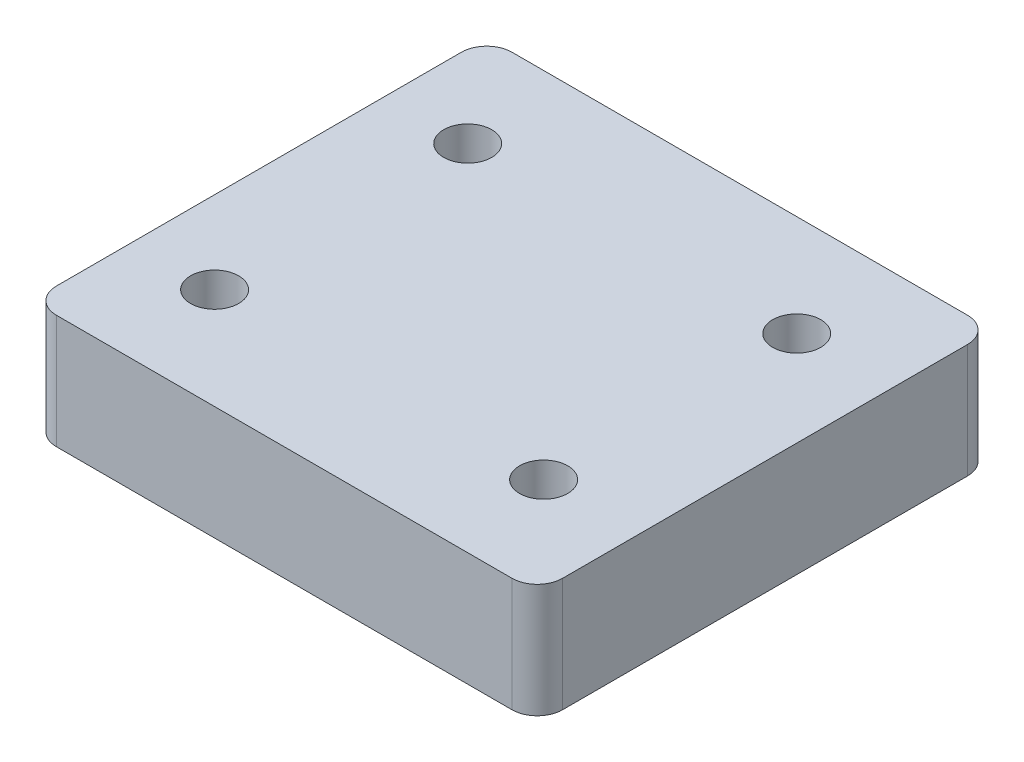
SolidWorks part; units mm, degrees
ref_plane "Front Plane" through (0, 0, 0) normal (0, 0, 1) x (1, 0, 0)
ref_plane "Top Plane" through (0, 0, 0) normal (0, 1, 0) x (1, 0, 0)
ref_plane "Right Plane" through (0, 0, 0) normal (1, 0, 0) x (0, 0, -1)
sketch "Sketch1" plane through (0, 0, 0) normal (0, 1, 0) x (1, 0, 0)
  line L1 (-10.5177, 16.6808) -> (29.4823, 16.6808)
  line L2 (-10.5177, 16.6808) -> (-10.5177, -19.3192)
  line L3 (-10.5177, -19.3192) -> (29.4823, -19.3192)
  line L4 (29.4823, 16.6808) -> (29.4823, -19.3192)
  dimension "D1" = 40
  dimension "D2" = 36
extrude "Boss-Extrude1" add sketch "Sketch1" along normal blind 9
sketch "Sketch2" plane through (0, 9, 0) normal (0, 1, 0) x (1, 0, 0)
  line L1 (-10.5177, -19.3192) -> (29.4823, -19.3192) construction
  line L2 (29.4823, 16.6808) -> (-10.5177, 16.6808) construction
  line L3 (29.4823, -19.3192) -> (29.4823, 16.6808) construction
  circle A0 centre (-4.0177, -11.3192) radius 1.9
  circle A1 centre (21.9823, -11.3192) radius 1.9
  circle A2 centre (-4.0177, 8.6808) radius 1.9
  circle A3 centre (21.9823, 8.6808) radius 1.9
  dimension "D1" = 26
  dimension "D3" = 8
  dimension "D6" = 7.5
  dimension "D2" = 8
  dimension "D4" = 26
  dimension "D5" = 20
extrude "Cut-Extrude1" cut sketch "Sketch2" against normal blind 10
fillet "Fillet1" radius 2 4 edges at (-10.5177, 4.5, -16.6808) (-10.5177, 4.5, 19.3192) (29.4823, 4.5, -16.6808) (29.4823, 4.5, 19.3192)
